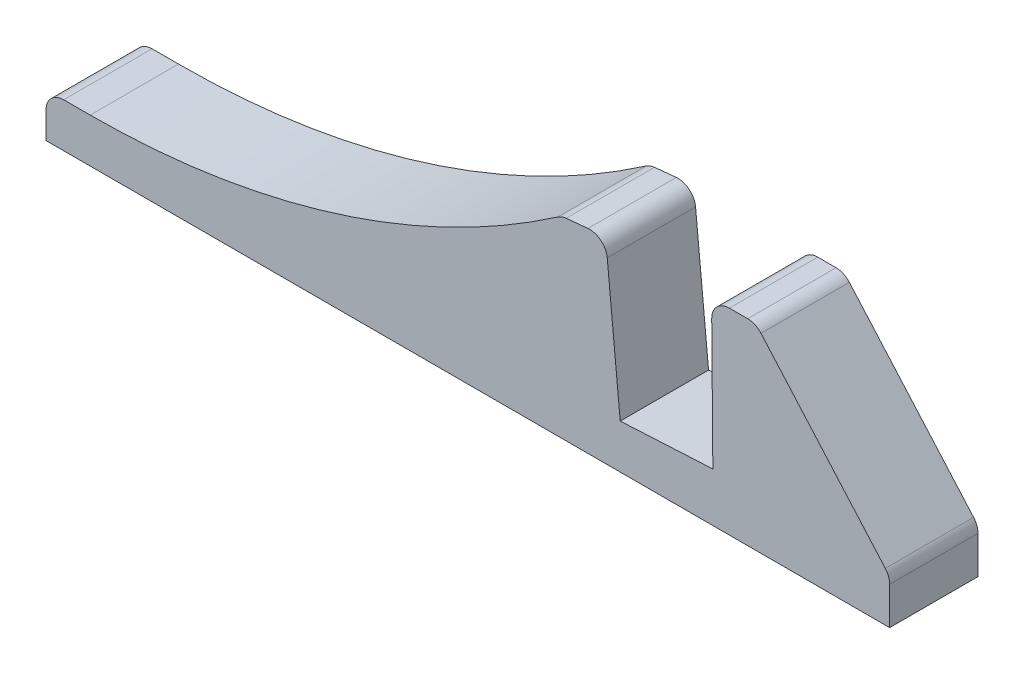
SolidWorks part; units mm, degrees
ref_plane "Plan de face" through (0, 0, 0) normal (0, 0, 1) x (1, 0, 0)
ref_plane "Plan de dessus" through (0, 0, 0) normal (0, 1, 0) x (1, 0, 0)
ref_plane "Plan de droite" through (0, 0, 0) normal (1, 0, 0) x (0, 0, -1)
sketch "Esquisse1" plane through (0, 0, 0) normal (0, 0, 1) x (1, 0, 0)
  line L0 (0, 0) -> (95.5, 0)
  line L1 (95.5, 0) -> (95.5, 5)
  line L2 (0, 0) -> (0, 5)
  line L3 (0, 5) -> (5, 5)
  line L4 (63.3389, 22.2515) -> (65, 5)
  line L5 (65, 5) -> (75.4856, 5.5495)
  line L6 (75.4856, 5.5495) -> (75.3399, 22.2515)
  line L9 (95.5, 5) -> (181.9518, 5) construction
  line L10 (70.2428, 5.2748) -> (69.3531, 22.2515) construction
  line L11 (63.3389, 22.2515) -> (58.3619, 21.7722)
  line L12 (63.3389, 22.2515) -> (210.7634, 22.2515) construction
  line L13 (75.3399, 22.2515) -> (80.3399, 22.2515)
  line L14 (80.3399, 22.2515) -> (95.5, 5)
  arc A3 (5, 5) -> (58.3619, 21.7722) centre (5, 98.2732) ccw
  point P11 (0, 0)
  point P12 (6.3483, 5)
  point P13 (72.7569, 39.1463)
  point P18 (83.2629, 38.9842)
  point P20 (81.83, 38.9842)
  point P21 (95.5, 5)
  dimension "D1" = 5
  dimension "D2" = 5
  dimension "D3" = 95.5
  dimension "D4" = 10.5
  dimension "D5" = 5
  dimension "D7" = 65
  dimension "D8" = 17
  dimension "D6" = 87
  dimension "D9" = 5
  dimension "D10" = 5
extrude "Boss.-Extru.1" add sketch "Esquisse1" along normal blind 10
fillet "Congé1" radius 2 6 edges at (0, 5, 5) (58.3619, 21.7722, 5) (63.3389, 22.2515, 5) (75.3399, 22.2515, 5) (80.3399, 22.2515, 5) (95.5, 5, 5)
equation "\"D3@Esquisse1\"=\"D7@Esquisse1\"+\"D4@Esquisse1\"+20"
equation "\"D9@Esquisse1\"=\"D5@Esquisse1\""
